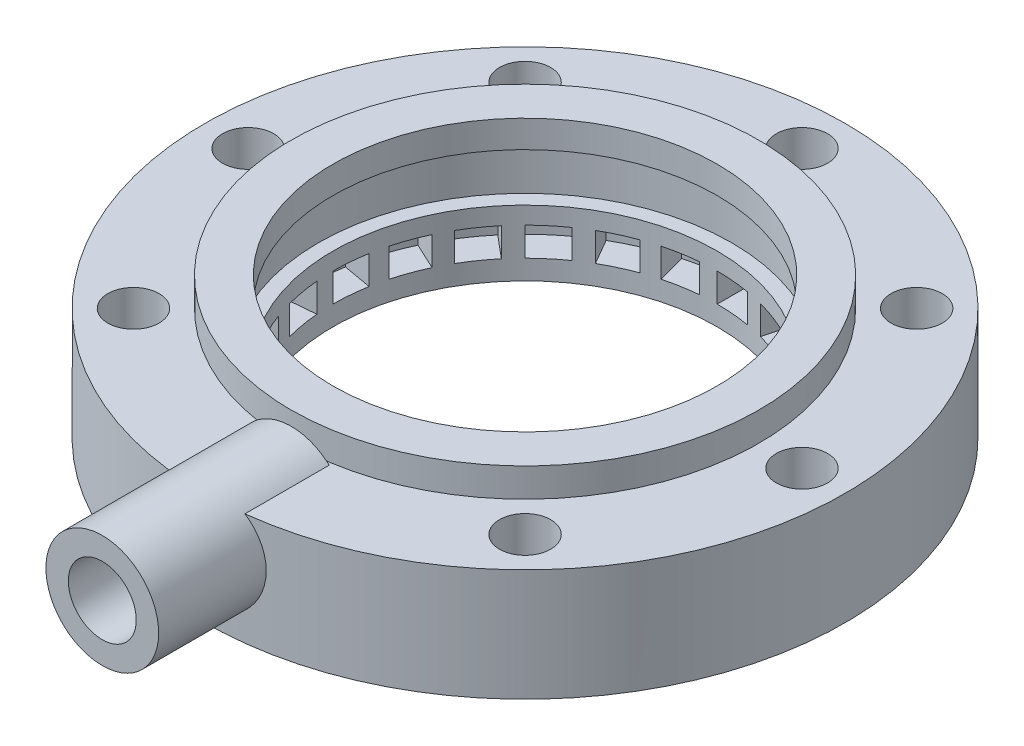
SolidWorks part; units mm, degrees
ref_plane "Front Plane" through (0, 0, 0) normal (0, 0, 1) x (1, 0, 0)
ref_plane "Top Plane" through (0, 0, 0) normal (0, 1, 0) x (1, 0, 0)
ref_plane "Right Plane" through (0, 0, 0) normal (1, 0, 0) x (0, 0, -1)
sketch "Sketch2" plane through (0, 0, 0) normal (0, 1, 0) x (1, 0, 0)
  circle A0 centre (0, 0) radius 100
sketch "Sketch3" plane through (0, 0, 0) normal (0, 1, 0) x (1, 0, 0)
  circle A0 centre (0, 0) radius 60
extrude "Boss-Extrude1" add sketch "Sketch2" along normal blind 35 contours A0
extrude "Cut-Extrude1" cut sketch "Sketch3" along normal blind 60 contours A0
sketch "Sketch4" plane through (0, 0, 0) normal (0, 1, 0) x (1, 0, 0)
  circle A0 centre (0, 0) radius 73
extrude "Boss-Extrude3" add sketch "Sketch4" along normal blind 44
sketch "Sketch5" plane through (0, 44, 0) normal (0, 1, 0) x (1, 0, 0)
  circle A0 centre (0, 0) radius 60
extrude "Cut-Extrude2" cut sketch "Sketch5" against normal blind 60
sketch "Sketch6" plane through (0, 35, 0) normal (0, 1, 0) x (1, 0, 0)
  line L0 (0, 0) -> (0, 100) construction
  line L1 (0, 50) -> (0, 100) construction
  line L2 (0, 100) -> (0, 72.9169) construction
  circle A0 centre (0, 0) radius 100 construction
  circle A1 centre (0, 86.4585) radius 8
  circle A2 centre (61.1354, 61.1354) radius 8
  circle A3 centre (86.4585, 0) radius 8
  circle A4 centre (61.1354, -61.1354) radius 8
  circle A6 centre (-61.1354, -61.1354) radius 8
  circle A7 centre (-86.4585, 0) radius 8
  circle A8 centre (-61.1354, 61.1354) radius 8
  circle A9 centre (0, -86.4585) radius 8 [skipped]
  point P25 (0, 0)
  dimension "D1" = 8
extrude "Cut-Extrude3" cut sketch "Sketch6" against normal through all
sketch "Sketch9" plane through (0, 0, 0) normal (0, 0, 1) x (1, 0, 0)
  line L0 (0, 44) -> (-60, 44) construction
  line L1 (73, 44) -> (-73, 44) construction
  line L2 (-60, 0) -> (0, 0) construction
  line L3 (-60, 44) -> (-60, 0) construction
  line L4 (0, 44) -> (0, 0) construction
  line L10 (-60, 15.0794) -> (-68, 15.0794)
  line L17 (-68, 6.1398) -> (-60, 6.1398)
  line L18 (-60, 15.0794) -> (-60, 6.1398)
  line L19 (-68, 15.0794) -> (-68, 6.1398)
revolve "Cut-Revolve2" cut sketch "Sketch9" angle 10 about L4
pattern_circular "CirPattern1" count 24 every 15 about axis through (0, 0, 0) along (0, 1, 0) skipping 6, 7 of "Cut-Revolve2"
sketch "Sketch10" plane through (0, 0, 0) normal (0, 0, 1) x (1, 0, 0)
  line L0 (-60, 44) -> (0, 44) construction
  line L1 (0, 44) -> (0, 0) construction
  line L2 (0, 0) -> (-60, 0) construction
  line L3 (-60, 0) -> (-60, 44) construction
  line L5 (-60, 35.5) -> (-64.5, 35.5)
  line L9 (-60, 20.5) -> (-64.5, 20.5)
  line L11 (-64.5, 20.5) -> (-64.5, 35.5)
  line L12 (-60, 35.5) -> (-60, 20.5)
  dimension "D1" = 4.5
revolve "Cut-Revolve4" cut sketch "Sketch10" angle 360 about L1
sketch "Sketch11" plane through (0, 0, 0) normal (0, 0, 1) x (1, 0, 0)
  line L0 (-73, 35) -> (-60, 35) construction
  line L2 (-60, 0) -> (-73, 0) construction
  line L3 (-73, 0) -> (-73, 35) construction
  line L4 (-60, 15.0794) -> (-73, 15.0794) construction
  line L5 (-73, 15.0794) -> (-73, 17.5) construction
  line L6 (-73, 17.5) -> (-70, 17.5) construction
  line L8 (-68, 15.0794) -> (-66.7121, 15.0794)
  line L17 (-60, 15.0794) -> (0, 15.0794) construction
  line L18 (0, 15.0794) -> (0, 35) construction
  line L19 (0, 35) -> (-60, 35) construction
  line L24 (-68, 15.0794) -> (-68, 6.1398) construction
  line L25 (-68, 20.1286) -> (-68, 15.0794)
  line L26 (-67.7412, 15.0794) -> (-65.683, 15.0794) construction
  line L27 (-66.7121, 15.0794) -> (-66.7121, 20.1286)
  line L28 (-66.7121, 20.1286) -> (-68, 20.1286)
  point P12 (-66.7121, 15.0794)
  dimension "D1" = 1.2879
ref_axis "Axis2" through (0, 46.2, 0) along (0, -1, 0)
revolve "Cut-Revolve9" cut sketch "Sketch11" angle 10 about L18
pattern_circular "CirPattern3" count 24 every 15 about axis through (0, 0, 0) along (0, 1, 0) skipping 17, 18 of "Cut-Revolve9"
sketch "Sketch12" plane through (0, 0, 0) normal (0, 0, 1) x (1, 0, 0)
  line L0 (-60, 44) -> (0, 44) construction
  line L1 (0, 44) -> (0, 0) construction
  line L2 (0, 0) -> (-60, 0) construction
  line L3 (-60, 0) -> (-60, 44) construction
  line L11 (-66.6354, 6.1398) -> (-66.6354, 31.236)
  line L13 (-66.6354, 6.1398) -> (-69.1354, 6.1398)
  line L14 (-69.1354, 6.1398) -> (-69.1354, 31.236)
  line L15 (-69.1354, 31.236) -> (-66.6354, 31.236)
  line L16 (-69.1354, 35) -> (-69.1354, 0) construction
  line L17 (-67.7412, 6.1398) -> (-59.7717, 6.1398) construction
  point P2 (-66.2749, 6.1398)
  point P3 (-69.1354, 19.1313)
  point P13 (-65.4924, 19.4503)
  point P14 (0, 0)
revolve "Cut-Revolve13" cut sketch "Sketch12" angle 10 about L1
pattern_circular "CirPattern4" count 24 every 15 about axis through (0, 0, 0) along (0, 1, 0) skipping 17, 18 of "Cut-Revolve13"
sketch "Sketch13" plane through (0, 0, 0) normal (0, 0, 1) x (1, 0, 0)
  line L0 (0, 44) -> (0, 0) construction
  line L1 (73, 44) -> (-73, 44) construction
ref_plane "Plane1" through (0, 0, 73) normal (0, 0, 1) x (1, 0, 0)
sketch "Sketch14" plane through (0, 0, 73) normal (0, 0, 1) x (1, 0, 0)
  line L0 (0, 44) -> (0, 0) construction
  line L1 (73, 44) -> (-73, 44) construction
  circle A0 centre (0, 22) radius 18.5
  circle A1 centre (0, 22) radius 15.5
sketch "Sketch16" plane through (0, 0, 73) normal (0, 0, 1) x (1, 0, 0)
  line L0 (0, 44) -> (0, 0) construction
  line L1 (60, 44) -> (-60, 44) construction
  circle A0 centre (0, 22) radius 14
  dimension "D1" = 28
extrude "Cut-Extrude4" cut sketch "Sketch16" along normal blind 34 and the other way blind 6
sketch "Sketch19" plane through (0, 0, 0) normal (0, 0, 1) x (1, 0, 0)
  line L0 (-69.1561, 31.321) -> (-69.1561, 18.7786)
  line L1 (-69.1561, 18.7786) -> (-66.676, 18.7786)
  line L2 (-66.676, 18.7786) -> (-66.676, 31.321)
  line L3 (-66.676, 31.321) -> (-69.1561, 31.321)
revolve "Cut-Revolve14" cut sketch "Sketch19" angle 360 about axis through (0, 46.2, 0) along (0, -1, 0)
sketch "Sketch20" plane through (0, 0, 73) normal (0, 0, 1) x (1, 0, 0)
  line L0 (0, 44) -> (0, 0) construction
  line L1 (73, 44) -> (-73, 44) construction
  circle A0 centre (0, 22) radius 14.1028
extrude "Extrude-Thin1" add sketch "Sketch20" along normal blind 59 separate body thin thin type mid plane wall 7
